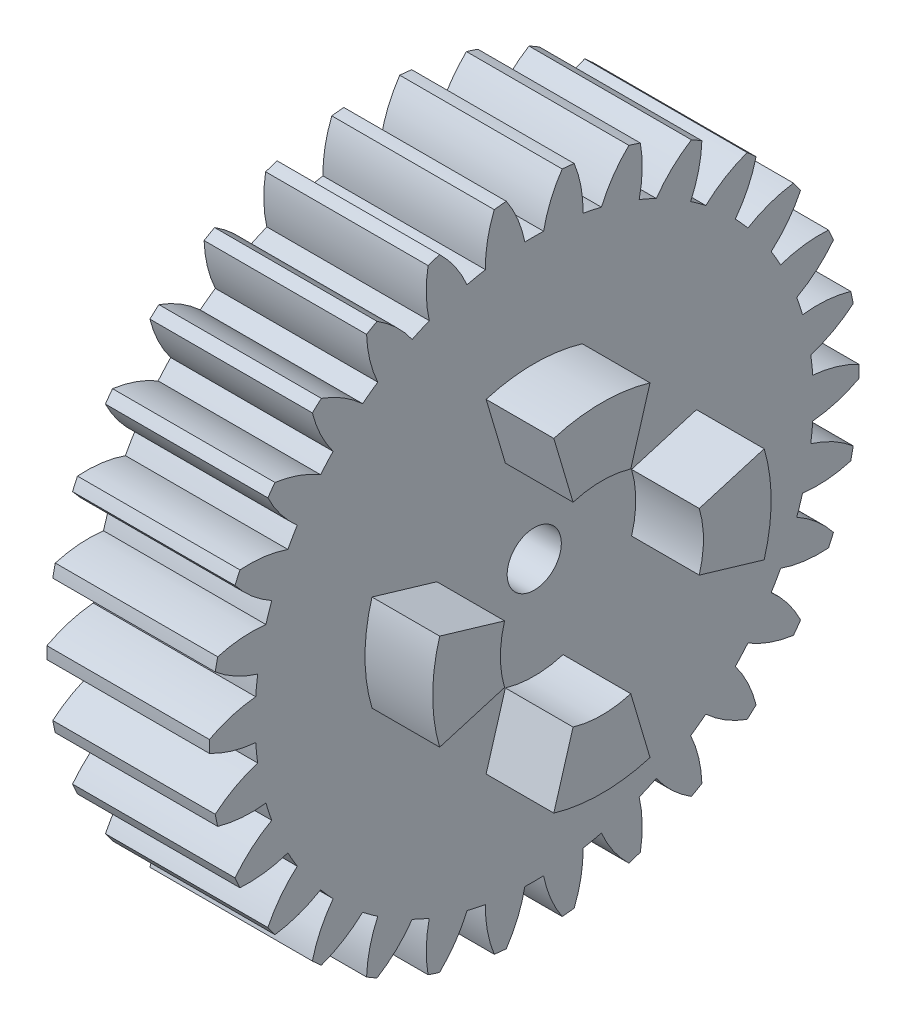
SolidWorks part; units mm, degrees
ref_plane "Plane1" through (0, 0, 0) normal (0, 0, 1) x (1, 0, 0)
ref_plane "Plane2" through (0, 0, 0) normal (0, 1, 0) x (1, 0, 0)
ref_plane "Plane3" through (0, 0, 0) normal (1, 0, 0) x (0, 0, -1)
sketch "HoldingSke" plane through (0, 0, 0) normal (0, 1, 0) x (1, 0, 0)
  line L0 (0, 0) -> (0.5774, -0.3333)
  line L1 (-15, 0) -> (100, 0) construction
  line L2 (0, 0) -> (-2.1039, 2.3779)
  line L3 (0, 0) -> (-11.863, 4.5341)
  line L4 (0, 0) -> (7.479, 4.318)
  line L5 (0, 0) -> (-46.8476, -17.4728)
  line L6 (0, 0) -> (-9.9476, -6.7116)
  line L7 (-2.1039, 2.3779) -> (8.6586, 51.2059)
  line L8 (-76.2, 54.61) -> (-75.5, 54.61)
  line L9 (-71.009, 38.7566) -> (-53.1078, 45.2721)
  line L10 (-76.2, 71.12) -> (104.1128, 71.12)
  line L11 (0, 0) -> (-12, 0)
  line L12 (-76.2, 101.6) -> (-76.147, 101.6)
  line L13 (24.9733, 27.94) -> (52.9518, 28.4284)
  line L14 (24.9733, 27.94) -> (24.9743, 27.94)
  line L15 (24.9733, 27.94) -> (100.4006, 29.5858)
  line L16 (-63.627, -1.5) -> (-12.827, -1.5)
  circle A0 centre (0, 0) radius 2
  circle A1 centre (0, 0) radius 20.624
  circle A2 centre (0, 0) radius 37.5
  circle A3 centre (0, 0) radius 2
  dimension "MHD" = 41.248
  dimension "Hub_dia" = 75
  dimension "Bore" = 4
  dimension "MBD" = 4
  dimension "Num_teeth" = 30
  dimension "Pitch" = 0.6667
  dimension "Overall_len" = 50
  dimension "Show_teeth" = 30
  dimension "Thickness" = 12
  dimension "OAL" = 50.0001
  dimension "T_dim" = 0.7
  dimension "Ap" = 20
  dimension "H" = 19.05
  dimension "Pitch_radius" = 180.3128
  dimension "Width" = 12
  dimension "Backlash" = 0.053
  dimension "Addendum_fac" = 1
  dimension "Dedendum_fac" = 1.25
  dimension "Clearance_fac" = 0.25
  dimension "Dedendum_add" = 0.001
  dimension "Module" = 1.5
sketch "BasProSke" plane through (0, 0, 0) normal (0, 1, 0) x (1, 0, 0)
  line L0 (-10, 0) -> (60, 0) construction
  line L1 (0, 0) -> (0, 24)
  line L2 (0, 0) -> (12, 0)
  line L3 (12, 0) -> (12, 24)
  line L4 (12, 24) -> (0, 24)
  dimension "Thickness" = 12
  dimension "Diameter" = 48
revolve "Base-Revolve" add sketch "BasProSke" angle 360 about L0
sketch "TooCutSke" plane through (0, 0, 0) normal (1, 0, 0) x (0, 0, -1)
  line L1 (0, 0) -> (0, 107) construction
  line L2 (0, 0) -> (-1.2703, 22.4641) construction
  line L3 (0, 0) -> (-4.6983, 44.7014) construction
  line L4 (-1.2703, 22.4641) -> (-2.3492, 22.3507) construction
  arc A0 (0.6933, 20.6123) -> (-0.6933, 20.6123) centre (0, 0) ccw
  arc A1 (2.0805, 23.9351) -> (-2.0805, 23.9351) centre (0, 0) ccw
  circle A2 centre (0, 0) radius 22.5 construction
  circle A3 centre (0, 0) radius 21.1431 construction
  arc A4 (-0.6933, 20.6123) -> (-2.0805, 23.9351) centre (-9.5243, 18.8764) ccw
  arc A5 (2.0805, 23.9351) -> (0.6933, 20.6123) centre (9.5243, 18.8764) ccw
  dimension "Root_dia" = 41.248
  dimension "Overcut_dia" = 48.0508
  dimension "Pitch_dia" = 45
  dimension "Base_dia" = 42.2862
  dimension "Flank_rad" = 9
  dimension "Half_ang" = 6
  dimension "Half_CT" = 1.0848
extrude "ToothCut" cut sketch "TooCutSke" along normal through all
fillet "Breaks" [suppressed] radius 0.03
fillet "RootFillets" [suppressed] radius 0.376
pattern_circular "TeethCuts" count 30 every 12 about axis through (-10, 0, 0) along (1, 0, 0) of "ToothCut", "RootFillets", "Breaks"
sketch "HubNeaOneSke" plane through (0, 0, 0) normal (-1, 0, 0) x (0, 0, 1)
  circle A0 centre (0, 0) radius 20.624
  dimension "Diameter" = 41.248
extrude "HubNearOne" [suppressed] add sketch "HubNeaOneSke" along normal blind 38.0001
sketch "HubNeaBotSke" plane through (0, 0, 0) normal (-1, 0, 0) x (0, 0, 1)
  circle A0 centre (0, 0) radius 20.624
  dimension "Diameter" = 41.248
extrude "HubNearBoth" [suppressed] add sketch "HubNeaBotSke" along normal blind 19
ref_plane "FarPln" through (12, 0, 0) normal (1, 0, 0) x (0, 0, -1)
sketch "HubFarSke" plane through (12, 0, 0) normal (1, 0, 0) x (0, 0, -1)
  circle A0 centre (0, 0) radius 20.624
  dimension "Diameter" = 41.248
extrude "HubFar" [suppressed] add sketch "HubFarSke" along normal blind 19
sketch "BorSke" plane through (0, 0, 0) normal (1, 0, 0) x (0, 0, -1)
  circle A0 centre (0, 0) radius 2
  dimension "Diameter" = 4
extrude "Bore" cut sketch "BorSke" along normal mid plane 100.0001
sketch "KeySke" plane through (0, 0, 0) normal (1, 0, 0) x (0, 0, -1)
  line L0 (-0.8, 0) -> (-0.8, 2.7)
  line L1 (-0.8, 2.7) -> (0.8, 2.7)
  line L2 (0.8, 2.7) -> (0.8, 0)
  line L3 (0, 0) -> (0, 34) construction
  line L4 (-0.8, 0) -> (0.8, 0)
  dimension "Offset" = 2.7
  dimension "Width" = 1.6
extrude "Keyway" [suppressed] cut sketch "KeySke" along normal mid plane 100.0001
pattern_circular "Keyway2" [suppressed] count 2 every 90 about axis through (-10, 0, 0) along (1, 0, 0)
sketch "草图1" plane through (12, 0, 0) normal (1, 0, 0) x (0, 0, -1)
  line L0 (-2.1318, 7.1906) -> (-3.553, 11.9844)
  line L1 (0, 7.5) -> (0, 12.5) construction
  line L2 (2.1318, 7.1906) -> (3.553, 11.9844)
  line L3 (7.1906, 2.1318) -> (11.9844, 3.553)
  line L4 (7.1906, -2.1318) -> (11.9844, -3.553)
  line L5 (2.1318, -7.1906) -> (3.553, -11.9844)
  line L6 (-2.1318, -7.1906) -> (-3.553, -11.9844)
  line L7 (-7.1906, -2.1318) -> (-11.9844, -3.553)
  line L8 (-7.1906, 2.1318) -> (-11.9844, 3.553)
  arc A0 (2.1318, 7.1906) -> (-2.1318, 7.1906) centre (0, 0) ccw
  arc A1 (3.553, 11.9844) -> (-3.553, 11.9844) centre (0, 0) ccw
  arc A2 (-3.553, 11.9844) -> (3.553, 11.9844) centre (0, 0) ccw construction
  arc A3 (-2.1318, 7.1906) -> (2.1318, 7.1906) centre (0, 0) ccw construction
  arc A4 (11.9844, -3.553) -> (11.9844, 3.553) centre (0, 0) ccw
  arc A5 (7.1906, -2.1318) -> (7.1906, 2.1318) centre (0, 0) ccw
  arc A6 (-3.553, -11.9844) -> (3.553, -11.9844) centre (0, 0) ccw
  arc A7 (-2.1318, -7.1906) -> (2.1318, -7.1906) centre (0, 0) ccw
  arc A8 (-11.9844, 3.553) -> (-11.9844, -3.553) centre (0, 0) ccw
  arc A9 (-7.1906, 2.1318) -> (-7.1906, -2.1318) centre (0, 0) ccw
  point P23 (0, 0)
  dimension "D1" = 25
  dimension "D2" = 15
  dimension "D3" = 4
extrude "凸台-拉伸1" add sketch "草图1" along normal blind 5
ref_plane "基准面1" through (6, 0, 0) normal (1, 0, 0) x (0, 0, -1)
mirror "镜向1" about plane through (6, 0, 0) normal (1, 0, 0) of "凸台-拉伸1"
equation "' \"Module@HoldingSke\" = 6.35"
equation "' \"Num_teeth@HoldingSke\" = 12"
equation "' \"Ap@HoldingSke\" =  20"
equation "' \"Ap@HoldingSke\" = 20"
equation "' \"Width@HoldingSke\" = 0.5 * 25.4"
equation "' \"Hub_dia@HoldingSke\"= 1 * 25.4"
equation "' \"Hub_dia@HoldingSke\" = 1 * 25.4"
equation "' \"Overall_len@HoldingSke\" = 1.0 * 25.4"
equation "' \"Bore@HoldingSke\" = 0.75 * 25.4"
equation "' \"T_dim@HoldingSke\" = 0.1 * 25.4"
equation "' \"Width@KeySke\" = 0.25 * 25.4"
equation "' \"Show_teeth@HoldingSke\" = 13"
equation "' \"Backlash@HoldingSke\" = 0.009 * 25.4"
equation "' \"Addendum_fac@HoldingSke\" = 1.0"
equation "' \"Dedendum_fac@HoldingSke\" = 1.25"
equation "' \"Dedendum_add@HoldingSke\" = 0.00005 * 25.4"
equation "' \"Clearance_fac@HoldingSke\" = 0.25"
equation "\"Pitch@HoldingSke\" = 1 / \"Module@HoldingSke\""
equation "\"Overcut_dia@TooCutSke\" = (\"Num_teeth@HoldingSke\" + 2 * \"Addendum_fac@HoldingSke\") / \"Pitch@HoldingSke\" + 0.002 * 25.4"
equation "\"Pitch_dia@TooCutSke\" = \"Num_teeth@HoldingSke\" / \"Pitch@HoldingSke\""
equation "\"Base_dia@TooCutSke\" = \"Num_teeth@HoldingSke\" / \"Pitch@HoldingSke\" * cos((\"Ap@HoldingSke\"  * 3.14159265 / 180))"
equation "\"Root_dia@TooCutSke\" = (\"Num_teeth@HoldingSke\" + 2) / \"Pitch@HoldingSke\" - 2 * (\"Addendum_fac@HoldingSke\" + \"Dedendum_fac@HoldingSke\") / \"Pitch@HoldingSke\" - \"Dedendum_add@HoldingSke\" * 2"
equation "\"Half_ang@TooCutSke\" = 180 / \"Num_teeth@HoldingSke\""
equation "\"Half_CT@TooCutSke\" = \"Num_teeth@HoldingSke\" / \"Pitch@HoldingSke\" * sin((3.14159265 / 2 / \"Num_teeth@HoldingSke\")) / 2 - 7 * \"Backlash@HoldingSke\" / 4"
equation "\"Flank_rad@TooCutSke\" = \"Num_teeth@HoldingSke\" / \"Pitch@HoldingSke\" / 5"
equation "\"Radius@RootFillets\" = \"Clearance_fac@HoldingSke\" / \"Pitch@HoldingSke\" + \"Dedendum_add@HoldingSke\""
equation "\"Break_rad@Breaks\" = 0.02 / \"Pitch@HoldingSke\""
equation "\"Thickness@HoldingSke\" = \"Width@HoldingSke\""
equation "\"OAL@HoldingSke\" = \"Thickness@HoldingSke\""
equation "\"MHD@HoldingSke\" = (\"Num_teeth@HoldingSke\" + 2) / \"Pitch@HoldingSke\" - 2 * (\"Addendum_fac@HoldingSke\" + \"Dedendum_fac@HoldingSke\")  / \"Pitch@HoldingSke\" - \"Dedendum_add@HoldingSke\" * 2"
equation "\"MBD@HoldingSke\" = (\"Num_teeth@HoldingSke\" + 2) / \"Pitch@HoldingSke\" - 2 * (\"Addendum_fac@HoldingSke\" + \"Dedendum_fac@HoldingSke\")  / \"Pitch@HoldingSke\" - \"Dedendum_add@HoldingSke\" * 2 - 0.002 * 25.4"
equation "\"MHD@HoldingSke\" = ((sgn( \"MHD@HoldingSke\" - \"Hub_dia@HoldingSke\" )-1)*( \"MHD@HoldingSke\" - \"Hub_dia@HoldingSke\" ))/-2+ \"Hub_dia@HoldingSke\""
equation "\"MBD@HoldingSke\" = ((sgn( \"MBD@HoldingSke\" - \"Bore@HoldingSke\" )-1)*( \"MBD@HoldingSke\" - \"Bore@HoldingSke\" ))/-2+ \"Bore@HoldingSke\""
equation "\"OAL@HoldingSke\" = ((sgn( \"OAL@HoldingSke\" - \"Overall_len@HoldingSke\" )+1)*( \"OAL@HoldingSke\" - \"Overall_len@HoldingSke\" ))/2 + \"Overall_len@HoldingSke\" + 0.000002 * 25.4"
equation "\"Num_teeth@TeethCuts\" = int( \"Show_teeth@HoldingSke\" ) + 1"
equation "\"Num_teeth@TeethCuts\" = ((sgn( \"Num_teeth@TeethCuts\" - \"Num_teeth@HoldingSke\" )-1)*( \"Num_teeth@TeethCuts\" - \"Num_teeth@HoldingSke\" ))/-2+ \"Num_teeth@HoldingSke\""
equation "\"Num_teeth@TeethCuts\" = ((sgn( \"Num_teeth@TeethCuts\" - 2.0)+1)*( \"Num_teeth@TeethCuts\" - 2.0))/2 +2.0"
equation "\"Angle@TeethCuts\" = 360.0 / \"Num_teeth@HoldingSke\""
equation "\"Diameter@BasProSke\" = (\"Num_teeth@HoldingSke\" + 2 * \"Addendum_fac@HoldingSke\") / \"Pitch@HoldingSke\""
equation "\"Thickness@BasProSke\"  = \"Thickness@HoldingSke\""
equation "' \"Fillet_rad@BasProSke\" =  \"Thickness@HoldingSke\" * 0.05"
equation "' \"Fillet_rad@BasProSke\" = \"Thickness@HoldingSke\" * 0.05"
equation "\"MHD@HoldingSke\" = ((sgn( \"MHD@HoldingSke\" - \"Root_dia@TooCutSke\" )-1)*( \"MHD@HoldingSke\" - \"Root_dia@TooCutSke\" ))/-2+ \"Root_dia@TooCutSke\""
equation "\"Diameter@HubNeaOneSke\" = \"MHD@HoldingSke\""
equation "\"Length@HubNearOne\" = \"OAL@HoldingSke\" - \"Thickness@BasProSke\""
equation "\"Diameter@HubNeaBotSke\" = \"MHD@HoldingSke\""
equation "\"Length@HubNearBoth\" = ( \"OAL@HoldingSke\" - \"Thickness@BasProSke\" ) / 2.0"
equation "\"Thickness@FarPln\" = \"Thickness@BasProSke\""
equation "\"Diameter@HubFarSke\" = \"MHD@HoldingSke\""
equation "\"Length@HubFar\" = ( \"OAL@HoldingSke\" - \"Thickness@BasProSke\" ) / 2.0"
equation "\"Diameter@BorSke\" = \"MBD@HoldingSke\""
equation "\"D1@Bore\" = \"OAL@HoldingSke\" * 2.0"
equation "\"D1@Keyway\" = \"OAL@HoldingSke\" * 2.0"
equation "\"Offset@KeySke\" = \"T_dim@HoldingSke\" + \"MBD@HoldingSke\" / 2.0"
